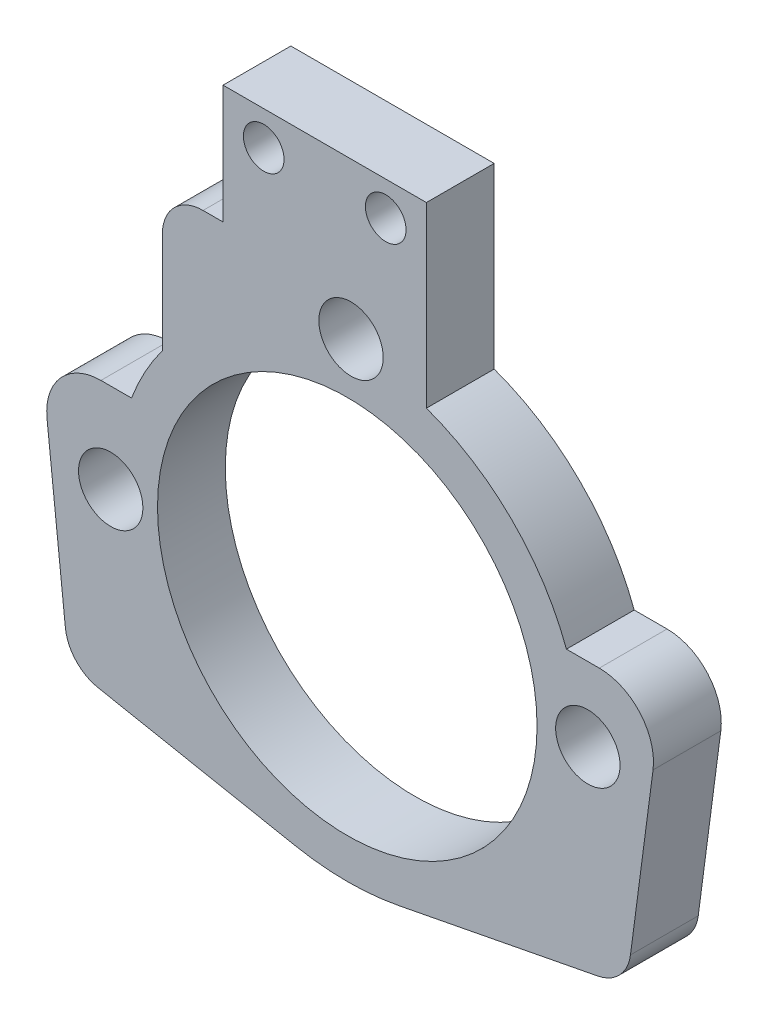
SolidWorks part; units mm, degrees
ref_plane "Front Plane" through (0, 0, 0) normal (0, 0, 1) x (1, 0, 0)
ref_plane "Top Plane" through (0, 0, 0) normal (0, 1, 0) x (1, 0, 0)
ref_plane "Right Plane" through (0, 0, 0) normal (1, 0, 0) x (0, 0, -1)
sketch "Sketch4" plane through (0, 0, 0) normal (0, 0, 1) x (1, 0, 0)
  line L0 (-14.0079, 0.0346) -> (13.4921, 0.0346) construction
  line L1 (-22.8989, 5.2452) -> (-20.8367, -14.0701)
  line L2 (-20.8367, -14.0701) -> (-0.2763, -18.0587)
  line L3 (-0.2763, -18.0587) -> (20.3335, -14.0701)
  line L4 (20.3335, -14.0701) -> (22.8745, 5.2452)
  line L5 (22.8745, 5.2452) -> (15.8907, 5.2452)
  line L6 (-22.8989, 5.2452) -> (-16.1938, 5.2452)
  line L8 (-9.44, 19.8711) -> (-13.9154, 19.8711)
  line L9 (-13.9154, 19.8711) -> (-13.9154, 9.4123)
  line L10 (0, 17.1137) -> (0, 28.6137) construction
  line L11 (0, 28.6137) -> (5.56, 28.6137)
  line L12 (0, 28.6137) -> (-9.44, 28.6137)
  line L13 (5.56, 28.6137) -> (5.56, 15.4741)
  line L15 (-9.44, 19.8711) -> (-9.44, 28.6137)
  circle A0 centre (-17.7298, -1.3529) radius 2.375
  circle A1 centre (0, 17.1137) radius 2.375
  circle A2 centre (17.4702, -0.2054) radius 2.375
  circle A3 centre (-0.2763, -0.7516) radius 14
  arc A4 (15.8907, 5.2452) -> (5.56, 15.4741) centre (-0.2763, -0.7516) ccw
  arc A6 (-16.1938, 5.2452) -> (-13.9154, 9.4123) centre (-0.2763, -0.7516) cw
  circle A7 centre (-6.44, 26.1137) radius 1.5
  circle A8 centre (2.56, 26.1137) radius 1.5
  point P20 (-17.5372, -1.5359)
  point P30 (-17.7298, -1.3529)
  point P32 (-17.6111, -1.6578)
  dimension "D2" = 4.75
  dimension "D3" = 28
  dimension "D4" = 4.75
  dimension "D5" = 4.75
  dimension "D9" = 3
  dimension "D10" = 3
  dimension "D1" = 27.5
  dimension "D6" = 11.5
  dimension "D7" = 5.56
  dimension "D8" = 9.44
  dimension "D11" = 3
  dimension "D12" = 3
  dimension "D13" = 2.5
  dimension "D14" = 2.5
  dimension "D15" = 24.6
  dimension "D16" = 25.6
  dimension "D17" = 35.2
extrude "Boss-Extrude1" add sketch "Sketch4" along normal blind 5
fillet "Fillet1" radius 4 2 edges at (22.8745, 5.2452, 2.5) (-22.8989, 5.2452, 2.5)
fillet "Fillet2" radius 3 2 edges at (20.3335, -14.0701, 2.5) (-20.8367, -14.0701, 2.5)
fillet "Fillet3" radius 20 1 edges at (-0.2763, -18.0587, 2.5)
fillet "Fillet4" radius 3 1 edges at (-13.9154, 19.8711, 2.5)
